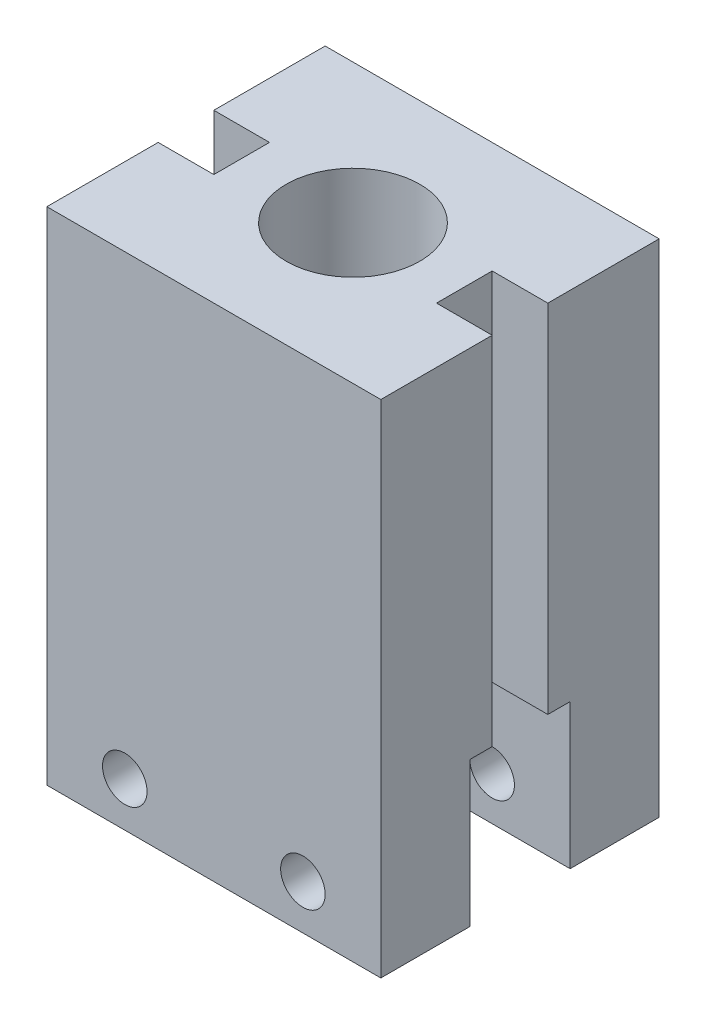
SolidWorks part; units mm, degrees
ref_plane "Front Plane" through (0, 0, 0) normal (0, 0, 1) x (1, 0, 0)
ref_plane "Top Plane" through (0, 0, 0) normal (0, 1, 0) x (1, 0, 0)
ref_plane "Right Plane" through (0, 0, 0) normal (1, 0, 0) x (0, 0, -1)
sketch "Sketch1" plane through (0, 0, 0) normal (0, 1, 0) x (1, 0, 0)
  line L1 (-15, 12.5) -> (15, 12.5)
  line L2 (-15, 12.5) -> (-15, -12.5)
  line L3 (-15, -12.5) -> (15, -12.5)
  line L4 (15, 12.5) -> (15, -12.5)
  line L5 (-15, 12.5) -> (15, -12.5) construction
  line L6 (-15, -12.5) -> (15, 12.5) construction
  point P0 (0, 0)
  dimension "D1" = 25
  dimension "D2" = 30
extrude "Boss-Extrude1" add sketch "Sketch1" along normal blind 45
sketch "Sketch2" plane through (0, 45, 0) normal (0, 1, 0) x (1, 0, 0)
  line L0 (15, -12.5) -> (15, 12.5) construction
  line L1 (15, 2.5) -> (10, 2.5)
  line L2 (15, 2.5) -> (15, -2.5)
  line L3 (15, -2.5) -> (10, -2.5)
  line L4 (10, 2.5) -> (10, -2.5)
  line L5 (0, 0) -> (19.7702, 0) construction
  line L6 (0, 11.9294) -> (0, -11.3083) construction
  line L7 (-15, -2.5) -> (-10, -2.5)
  line L8 (-10, 2.5) -> (-10, -2.5)
  line L9 (-15, 2.5) -> (-10, 2.5)
  line L10 (-15, 2.5) -> (-15, -2.5)
  dimension "D1" = 5
  dimension "D2" = 5
  dimension "D3" = 2.5
extrude "Cut-Extrude1" cut sketch "Sketch2" against normal blind 45
sketch "Sketch4" plane through (0, 0, -12.5) normal (0, 0, -1) x (-1, 0, 0)
  line L0 (-8, 4) -> (8, 4) construction
  line L1 (15, 45) -> (15, 0) construction
  line L2 (-15, 0) -> (15, 0) construction
  line L3 (-15, 45) -> (-15, 0) construction
  circle A0 centre (8, 4) radius 2
  circle A1 centre (-8, 4) radius 2
  dimension "D4" = 4
  dimension "D1" = 7
  dimension "D2" = 4
  dimension "D3" = 7
extrude "Cut-Extrude17" cut sketch "Sketch4" against normal blind 9
sketch "Sketch5" plane through (-15, 0, 0) normal (-1, 0, 0) x (0, 0, 1)
  line L0 (-12.5, 0) -> (-2.5, 0) construction
  line L1 (-4.5, 0) -> (4.5, 0)
  line L2 (-4.5, 0) -> (-4.5, 13)
  line L3 (-4.5, 13) -> (4.5, 13)
  line L4 (4.5, 0) -> (4.5, 13)
  line L5 (0, 13) -> (0, 0) construction
  dimension "D1" = 13
  dimension "D2" = 9
extrude "Cut-Extrude18" cut sketch "Sketch5" against normal through all
sketch "Sketch6" plane through (0, 0, 12.5) normal (0, 0, 1) x (1, 0, 0)
  circle A0 centre (8, 4) radius 2
  circle A1 centre (-8, 4) radius 2
extrude "Cut-Extrude19" cut sketch "Sketch6" against normal blind 9
sketch "Sketch7" plane through (0, 45, 0) normal (0, 1, 0) x (1, 0, 0)
  circle A0 centre (0, 0) radius 6
  dimension "D1" = 12
extrude "Cut-Extrude20" cut sketch "Sketch7" against normal through all
